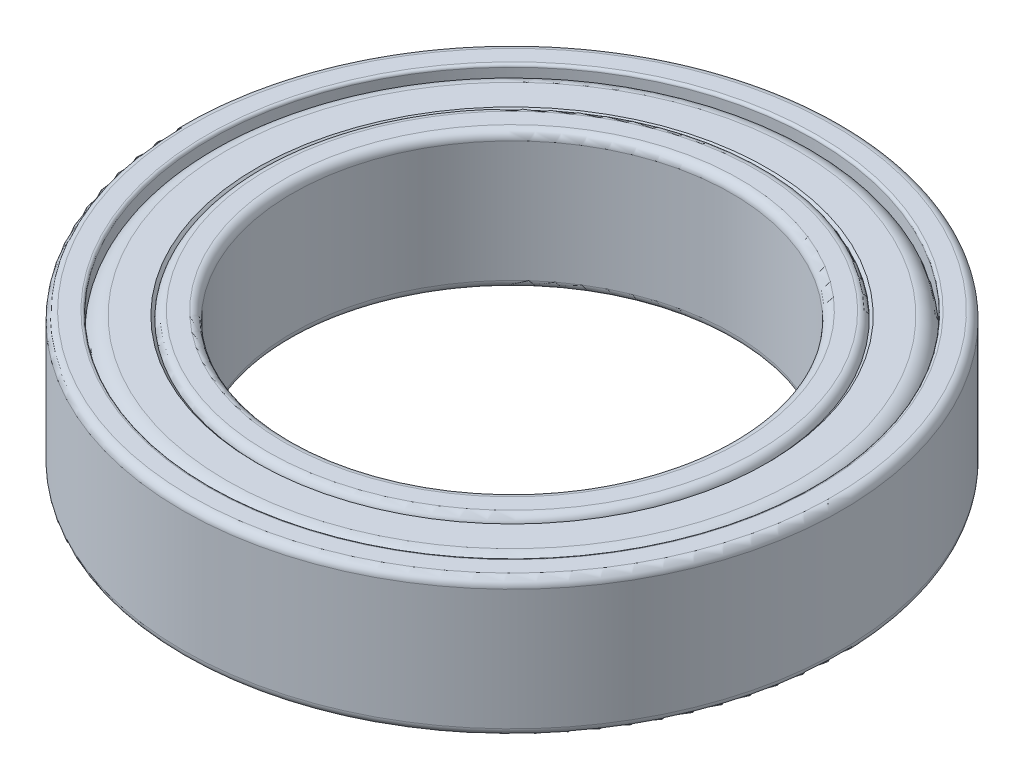
SolidWorks part; units mm, degrees
material "1060 Alloy"
ref_plane "Front Plane" through (0, 0, 0) normal (0, 0, 1) x (1, 0, 0)
ref_plane "Top Plane" through (0, 0, 0) normal (0, 1, 0) x (1, 0, 0)
ref_plane "Right Plane" through (0, 0, 0) normal (1, 0, 0) x (0, 0, -1)
sketch "Sketch1" plane through (0, 0, 0) normal (0, 1, 0) x (1, 0, 0)
  circle A0 centre (0, 0) radius 6
  circle A1 centre (0, 0) radius 5.5
  circle A2 centre (0, 0) radius 4
  circle A3 centre (0, 0) radius 4.6
  dimension "D1" = 12
  dimension "D2" = 0.5
  dimension "D3" = 8
  dimension "D4" = 0.6
extrude "Boss-Extrude1" add sketch "Sketch1" along normal mid plane 2.5 contours A0 A1 | A3 A2
fillet "Fillet1" radius 0.15 4 edges at (0, -1.25, 4) (0, 1.25, 4) (0, -1.25, 4.6) (0, 1.25, 4.6)
fillet "Fillet2" radius 0.15 2 edges at (0, -1.25, 6) (0, 1.25, 6)
fillet "Fillet3" radius 0.05 2 edges at (0, -1.25, 5.5) (0, 1.25, 5.5)
sketch "Sketch2" plane through (0, 0, 0) normal (0, 1, 0) x (1, 0, 0)
  circle A0 centre (0, 0) radius 5.5
  circle A1 centre (0, 0) radius 4.6
  circle A2 centre (0, 0) radius 5.5 construction
  circle A3 centre (0, 0) radius 4.6 construction
extrude "Boss-Extrude2" add sketch "Sketch2" along normal mid plane 2.35 separate body
fillet "Fillet4" radius 0.3 2 edges at (0, -1.175, 5.5) (0, 1.175, 5.5)
chamfer "Chamfer1" distance 0.05 angle 45 2 edges at (0, -1.175, 4.6) (0, 1.175, 4.6)
